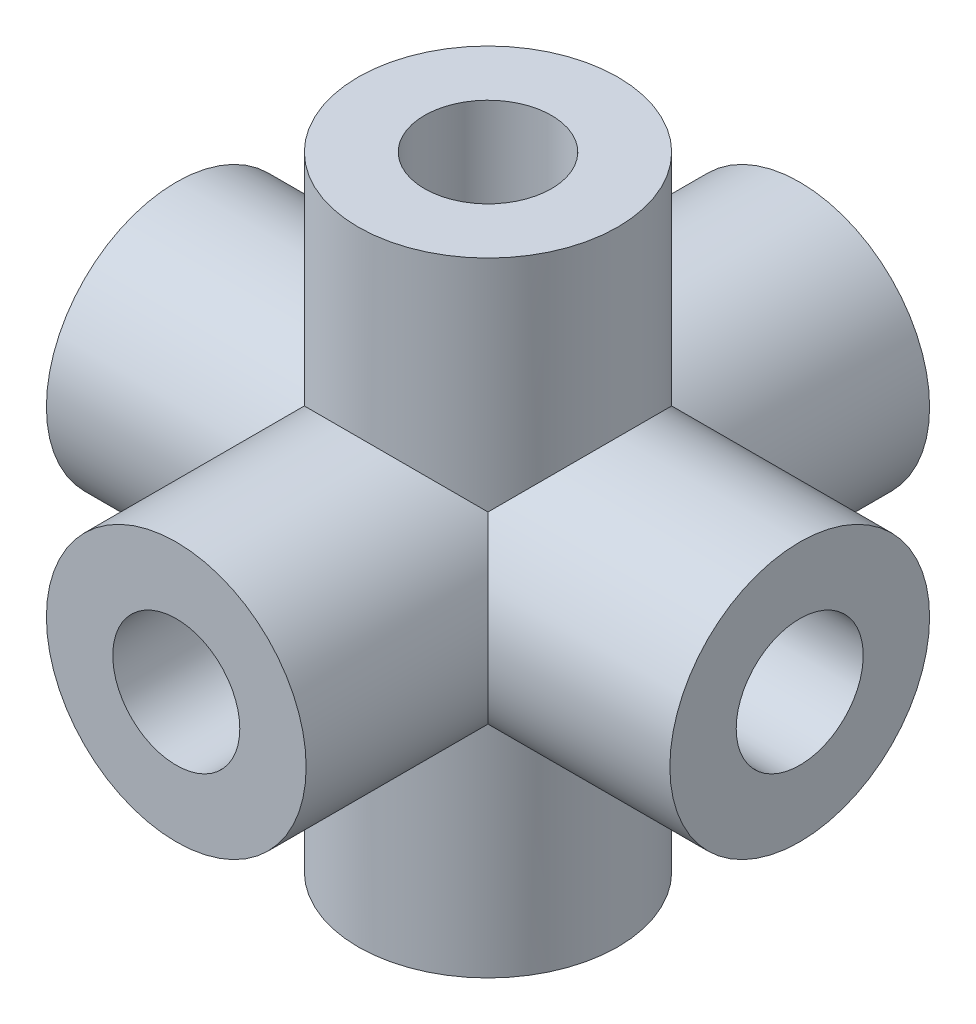
SolidWorks part; units mm, degrees
material "PS HI"
ref_plane "Ön Düzlem" through (0, 0, 0) normal (0, 0, 1) x (1, 0, 0)
ref_plane "Üst Düzlem" through (0, 0, 0) normal (0, 1, 0) x (1, 0, 0)
ref_plane "Sağ Düzlem" through (0, 0, 0) normal (1, 0, 0) x (0, 0, -1)
sketch "Çizim1" plane through (0, 0, 0) normal (0, 0, 1) x (1, 0, 0)
  circle A0 centre (0, 0) radius 5
  dimension "D1" = 10
extrude "Yükseklik-Ekstrüzyon1" add sketch "Çizim1" along normal mid plane 24
sketch "Çizim2" plane through (0, 0, 0) normal (0, 1, 0) x (1, 0, 0)
  circle A0 centre (0, 0) radius 5
extrude "Yükseklik-Ekstrüzyon2" add sketch "Çizim2" along normal mid plane 24
sketch "Çizim3" plane through (0, 0, 0) normal (1, 0, 0) x (0, 0, -1)
  circle A0 centre (0, 0) radius 5
  dimension "D1" = 10
extrude "Yükseklik-Ekstrüzyon3" add sketch "Çizim3" along normal mid plane 24
sketch "Çizim4" plane through (-12, 0, 0) normal (-1, 0, 0) x (0, 0, 1)
  circle A0 centre (0, 0) radius 2.445
  dimension "D1" = 4.89
extrude "Kes-Ekstrüzyon1" cut sketch "Çizim4" against normal blind 6
mirror "Aynalama1" about plane through (0, 0, 0) normal (1, 0, 0) of "Kes-Ekstrüzyon1"
sketch "Çizim5" plane through (0, 0, 12) normal (0, 0, 1) x (1, 0, 0)
  circle A0 centre (0, 0) radius 2.445
  dimension "D1" = 4.89
extrude "Kes-Ekstrüzyon2" cut sketch "Çizim5" against normal blind 6
mirror "Aynalama2" about plane through (0, 0, 0) normal (0, 0, 1) of "Kes-Ekstrüzyon2"
sketch "Çizim6" plane through (0, 12, 0) normal (0, 1, 0) x (1, 0, 0)
  circle A0 centre (0, 0) radius 2.445
  dimension "D1" = 4.89
extrude "Kes-Ekstrüzyon3" cut sketch "Çizim6" against normal blind 6
mirror "Aynalama3" about plane through (0, 0, 0) normal (0, 1, 0) of "Kes-Ekstrüzyon3"
